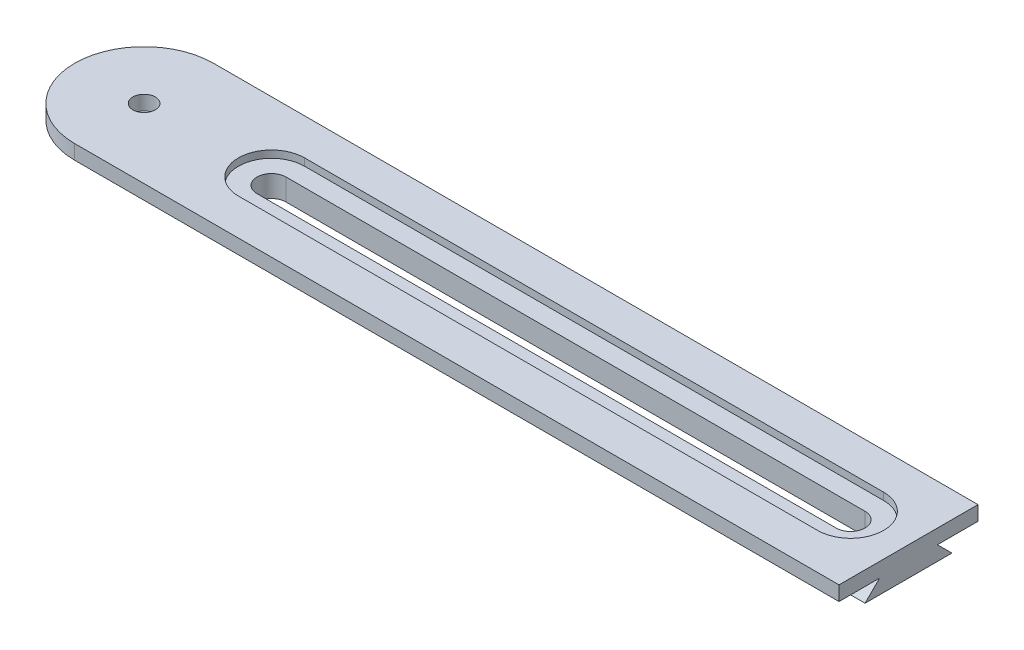
SolidWorks part; units mm, degrees
ref_plane "Front Plane" through (0, 0, 0) normal (0, 0, 1) x (1, 0, 0)
ref_plane "Top Plane" through (0, 0, 0) normal (0, 1, 0) x (1, 0, 0)
ref_plane "Right Plane" through (0, 0, 0) normal (1, 0, 0) x (0, 0, -1)
sketch "Sketch1" plane through (0, 0, 0) normal (0, 1, 0) x (1, 0, 0)
  line L1 (0, 0) -> (152.4, 0)
  line L2 (0, 0) -> (0, 30.48)
  line L3 (0, 30.48) -> (152.4, 30.48)
  line L4 (152.4, 0) -> (152.4, 30.48)
  dimension "D1" = 152.4
  dimension "D2" = 30.48
extrude "Boss-Extrude1" add sketch "Sketch1" along normal blind 6.35
sketch "Sketch2" plane through (0, 6.35, 0) normal (0, 1, 0) x (1, 0, 0)
  line L0 (12.7, 15.24) -> (139.7, 15.24) construction
  line L1 (12.7, 18.415) -> (139.7, 18.415)
  line L2 (12.7, 12.065) -> (139.7, 12.065)
  line L3 (0, 30.48) -> (0, 0) construction
  line L4 (152.4, 0) -> (152.4, 30.48) construction
  line L5 (152.4, 30.48) -> (0, 30.48) construction
  arc A0 (12.7, 18.415) -> (12.7, 12.065) centre (12.7, 15.24) ccw
  arc A1 (139.7, 12.065) -> (139.7, 18.415) centre (139.7, 15.24) ccw
  point P2 (76.2, 15.24)
  dimension "D1" = 12.7
  dimension "D2" = 12.7
  dimension "D3" = 15.24
  dimension "D4" = 6.35
extrude "Cut-Extrude1" cut sketch "Sketch2" against normal through all
sketch "Sketch3" plane through (0, 6.35, 0) normal (0, 1, 0) x (1, 0, 0)
  line L0 (12.7, 15.24) -> (139.7, 15.24) construction
  line L1 (12.7, 22.4937) -> (139.7, 22.4937)
  line L2 (12.7, 7.9863) -> (139.7, 7.9863)
  arc A0 (12.7, 22.4937) -> (12.7, 7.9863) centre (12.7, 15.24) ccw
  arc A1 (139.7, 7.9863) -> (139.7, 22.4937) centre (139.7, 15.24) ccw
  point P4 (76.2, 15.24)
  dimension "D1" = 7.2537
extrude "Cut-Extrude2" cut sketch "Sketch3" against normal blind 1.5875
sketch "Sketch4" plane through (0, 0, 0) normal (-1, 0, 0) x (0, 0, 1)
  line L0 (-30.48, 0) -> (0, 0) construction
  line L5 (-21.59, 3.175) -> (-24.765, 0)
  line L6 (-8.89, 3.175) -> (-5.715, 0)
  line L7 (-21.59, 3.175) -> (-30.48, 3.175)
  line L8 (-30.48, 6.35) -> (-30.48, 0) construction
  line L9 (-8.89, 3.175) -> (0, 3.175)
  line L10 (0, 6.35) -> (0, 0) construction
  line L11 (-30.48, 3.175) -> (-30.48, 0)
  line L12 (-5.715, 0) -> (0, 0)
  line L15 (-30.48, 0) -> (0, 0)
  line L16 (0, 0) -> (0, 6.35)
  line L17 (0, 6.35) -> (-30.48, 6.35)
  line L18 (-30.48, 6.35) -> (-30.48, 0)
  line L19 (-30.48, 0) -> (-24.765, 0)
  line L20 (0, 0) -> (0, 3.175)
  line L22 (-30.48, 3.175) -> (-30.48, 0)
  dimension "D1" = 12.7
  dimension "D3" = 45
  dimension "D4" = 45
  dimension "D5" = 0
extrude "Cut-Extrude3" cut sketch "Sketch4" against normal through all contours L6 L12 L20 L9
ref_plane "Plane1" through (0, 0, -15.24) normal (0, 0, -1) x (-1, 0, 0)
mirror "Mirror1" about plane through (0, 0, -15.24) normal (0, 0, -1) of "Cut-Extrude3"
sketch "Sketch8" plane through (0, 6.35, 0) normal (0, 1, 0) x (1, 0, 0)
  line L0 (0, 15.24) -> (-15.24, 15.24) construction
  line L1 (0, 30.48) -> (0, 0) construction
  line L2 (0, 0) -> (-15.24, 0)
  line L3 (0, 30.48) -> (-15.24, 30.48)
  line L5 (0, 30.48) -> (0, 0)
  arc A1 (-15.24, 30.48) -> (-15.24, 0) centre (-15.24, 15.24) ccw
  point P9 (0, 15.24)
  point P10 (0, 0)
  point P12 (0, 0)
  point P13 (-7.6962, 14.6812)
  point P14 (-9.0358, 14.2823)
  dimension "D3" = 15.24
  dimension "D1" = 15.24
  dimension "D2" = 15.24
  dimension "D4" = 15.24
extrude "Boss-Extrude2" add sketch "Sketch8" against normal up to surface (3.175 mm away) contours A1 L2 L5 L3 up to face at (76.2, 3.175, -26.035)
hole_wizard "#8 Clearance Hole1" positions "Sketch9" profile "Sketch10" hole size "#8" standard "ANSI Inch" end condition up to next
sketch "Sketch9" plane through (0, 6.35, 0) normal (0, 1, 0) x (1, 0, 0)
  point P0 (-15.24, 15.24)
sketch "Sketch10" plane through (-15.24, 6.35, -15.24) normal (1, 0, 0) x (0, 0, 1)
  line L0 (0, 0) -> (0, 3.175)
  line L1 (0, 3.175) -> (2.4574, 3.175)
  line L2 (2.4574, 3.175) -> (2.4574, 0)
  line L5 (2.4574, 0) -> (0, 0)
  line L11 (0, -6.35) -> (0, 107.95) construction
  dimension "Thru Hole Dia." = 4.9149
  dimension "Thru Hole Depth" = 3.175
